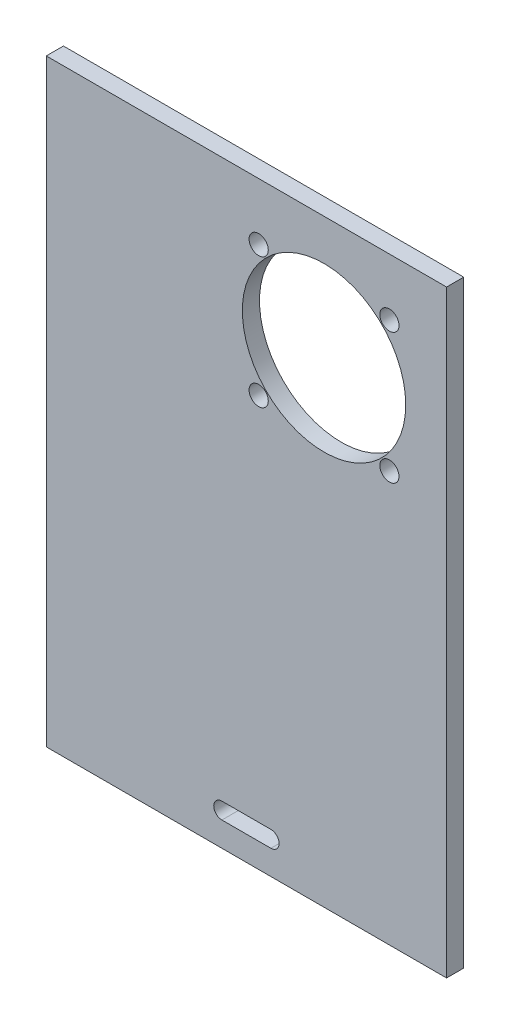
SolidWorks part; units mm, degrees
ref_plane "Front Plane" through (0, 0, 0) normal (0, 0, 1) x (1, 0, 0)
ref_plane "Top Plane" through (0, 0, 0) normal (0, 1, 0) x (1, 0, 0)
ref_plane "Right Plane" through (0, 0, 0) normal (1, 0, 0) x (0, 0, -1)
sketch "Sketch1" plane through (0, 0, 0) normal (0, 0, 1) x (1, 0, 0)
  line L1 (-24.7663, 39.1467) -> (73.2337, 39.1467)
  line L2 (-24.7663, 39.1467) -> (-24.7663, -107.3533)
  line L3 (-24.7663, -107.3533) -> (73.2337, -107.3533)
  line L4 (73.2337, 39.1467) -> (73.2337, -107.3533)
  dimension "D1" = 98
  dimension "D2" = 146.5
extrude "Boss-Extrude1" add sketch "Sketch1" along normal blind 4.2
sketch "Sketch3" plane through (0, 0, 4.2) normal (0, 0, 1) x (1, 0, 0)
  line L0 (73.2337, -107.3533) -> (73.2337, 39.1467) construction
  line L1 (73.2337, 39.1467) -> (-24.7663, 39.1467) construction
  circle A0 centre (43.2337, 9.1467) radius 20
  dimension "D1" = 40
  dimension "D2" = 30
  dimension "D3" = 30
extrude "Cut-Extrude2" cut sketch "Sketch3" against normal blind 10
sketch "Sketch4" plane through (0, 0, 4.2) normal (0, 0, 1) x (1, 0, 0)
  circle A1 centre (27.2337, 25.1467) radius 2.35
  circle A2 centre (59.2337, 25.1467) radius 2.35
  circle A3 centre (59.2337, -6.8533) radius 2.35
  circle A4 centre (27.2337, -6.8533) radius 2.35
  dimension "D7" = 4.7
  dimension "D10" = 4.7
  dimension "D11" = 4.7
  dimension "D16" = 4.7
extrude "Cut-Extrude3" cut sketch "Sketch4" against normal blind 10
sketch "Sketch6" plane through (0, 0, 4.2) normal (0, 0, 1) x (1, 0, 0)
  line L0 (18.2337, -99.3533) -> (30.2337, -99.3533) construction
  line L1 (18.2337, -97.3533) -> (30.2337, -97.3533)
  line L2 (18.2337, -101.3533) -> (30.2337, -101.3533)
  line L3 (-24.7663, -107.3533) -> (73.2337, -107.3533) construction
  line L4 (-24.7663, 39.1467) -> (-24.7663, -107.3533) construction
  line L5 (73.2337, -107.3533) -> (73.2337, 39.1467) construction
  arc A0 (18.2337, -97.3533) -> (18.2337, -101.3533) centre (18.2337, -99.3533) ccw
  arc A1 (30.2337, -101.3533) -> (30.2337, -97.3533) centre (30.2337, -99.3533) ccw
  point P2 (24.2337, -99.3533)
  dimension "D1" = 4
  dimension "D2" = 8
  dimension "D3" = 43
  dimension "D4" = 43
extrude "Cut-Extrude5" cut sketch "Sketch6" against normal through all
